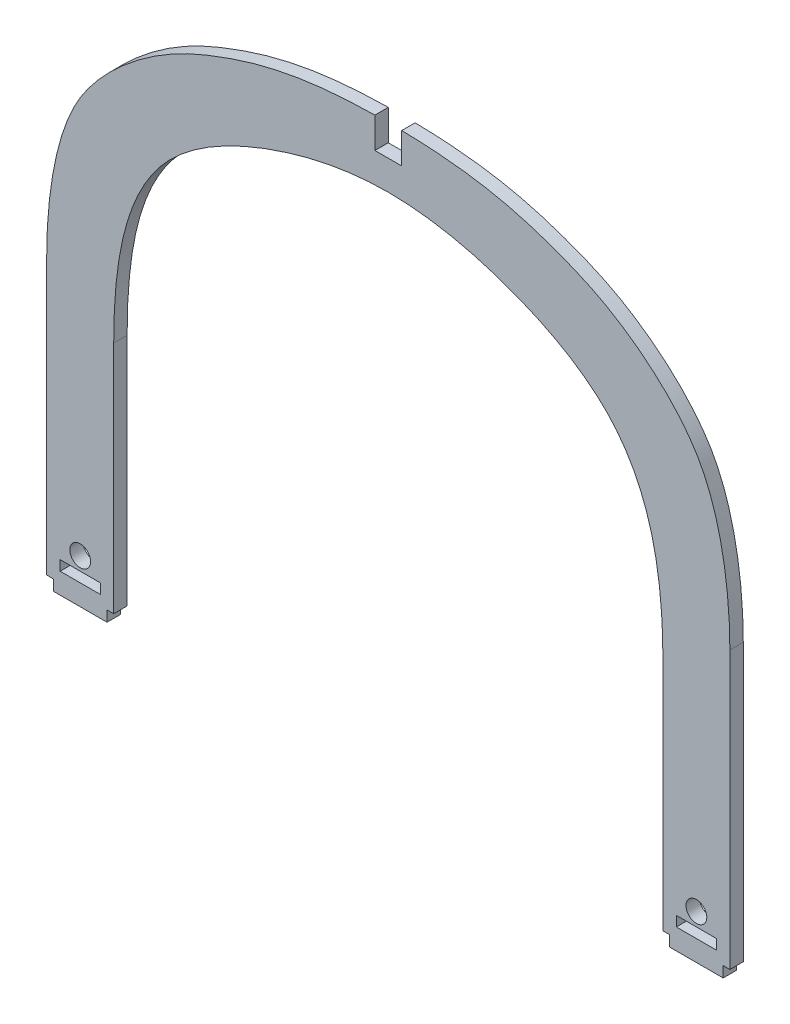
SolidWorks part; units mm, degrees
ref_plane "前视基准面" through (0, 0, 0) normal (0, 0, 1) x (1, 0, 0)
ref_plane "上视基准面" through (0, 0, 0) normal (0, 1, 0) x (1, 0, 0)
ref_plane "右视基准面" through (0, 0, 0) normal (1, 0, 0) x (0, 0, -1)
sketch "草图1" plane through (0, 0, 0) normal (0, 0, 1) x (1, 0, 0)
  line L0 (0, 0) -> (1, 0)
  line L1 (10, 0) -> (10, 35)
  line L2 (0, 0) -> (0, 41.3187)
  line L3 (10, 0) -> (92, 0) construction
  line L4 (51, 0) -> (51, 91.6216) construction
  line L5 (92, 35) -> (92, 0)
  line L6 (92, 0) -> (93, 0)
  line L7 (102, 0) -> (102, 41.3187)
  line L8 (93, -1.6) -> (101, -1.6)
  line L9 (101, -1.6) -> (101, 0)
  line L10 (93, -1.6) -> (93, 0)
  line L11 (9, -1.6) -> (9, 0)
  line L12 (9, -1.6) -> (1, -1.6)
  line L13 (1, -1.6) -> (1, 0)
  line L14 (101, 0) -> (102, 0)
  line L15 (9, 0) -> (10, 0)
  spline S0 degree 3 poles (0, 41.3187) (0, 48.3906) (1.3251, 58.8307) (8.6719, 69.8334) (16.3976, 76.0794) (30.7396, 82.0516) (39.3613, 84) (51, 84) knots 0 0 0 0 0.315307 0.38076 0.624111 0.689077 1 1 1 1
  spline S1 degree 3 poles (102, 41.3187) (102, 48.3906) (100.6749, 58.8307) (93.3281, 69.8334) (85.6024, 76.0794) (71.2604, 82.0516) (62.6387, 84) (51, 84) knots 0 0 0 0 0.315307 0.38076 0.624111 0.689077 1 1 1 1
  spline S2 degree 3 poles (92, 35) (92, 45.9589) (89.1979, 61.8504) (68.861, 72.6058) (56.8497, 75) (51, 75) knots 0 0 0 0 0.441101 0.721666 1 1 1 1
  spline S3 degree 3 poles (10, 35) (10, 45.9589) (12.8021, 61.8504) (33.139, 72.6058) (45.1503, 75) (51, 75) knots 0 0 0 0 0.441101 0.721666 1 1 1 1
  point P15 (97, -1.6)
  dimension "D1" = 10
  dimension "D2" = 35
  dimension "D3" = 82
  dimension "D4" = 8
  dimension "D5" = 1
  dimension "D6" = 1.6
  dimension "D7" = 9
  dimension "D8" = 40
extrude "保护罩主体" add sketch "草图1" along normal blind 2
sketch "上槽口" plane through (0, 0, 0) normal (0, 0, -1) x (-1, 0, 0)
  line L0 (-53, 79.4) -> (-49, 79.4)
  line L1 (-49, 79.4) -> (-49, 86)
  line L4 (-10, 35) -> (-92, 35) construction
  line L5 (-51, 35) -> (-51, 58.4038) construction
  line L6 (-49, 86) -> (-53, 86)
  line L7 (-53, 86) -> (-53, 79.4)
  dimension "D1" = 2
  dimension "D2" = 4
  dimension "D3" = 4.6
extrude "错孔_上" cut sketch "上槽口" against normal through all
sketch "安装孔" plane through (0, 0, 0) normal (0, 0, -1) x (-1, 0, 0)
  line L0 (-92, 0) -> (-93, 0) construction
  line L1 (-51, 86) -> (-51, -18.3042) construction
  line L2 (-92, 35) -> (-92, 0) construction
  circle A0 centre (-97, 5) radius 1.55
  circle A2 centre (-5, 5) radius 1.55
  dimension "D1" = 5
  dimension "D2" = 3.1
  dimension "D3" = 5
extrude "安装孔_" cut sketch "安装孔" against normal through all
sketch "草图4" plane through (0, 0, 0) normal (0, 0, -1) x (-1, 0, 0)
  line L0 (-100, 1.5) -> (-94, 1.5)
  line L1 (-94, 1.5) -> (-94, 3)
  line L2 (-94, 3) -> (-100, 3)
  line L8 (-100, 3) -> (-100, 1.5)
  line L9 (-101, 0) -> (-102, 0) construction
  line L11 (-93, 0) -> (-93, -1.6) construction
  line L12 (-92, 0) -> (-10, 0) construction
  line L13 (-51, 0) -> (-51, 26.9655) construction
  line L14 (-8, 1.5) -> (-8, 3)
  line L15 (-2, 1.5) -> (-8, 1.5)
  line L16 (-2, 3) -> (-2, 1.5)
  line L17 (-8, 3) -> (-2, 3)
  dimension "D1" = 6
  dimension "D2" = 1.5
  dimension "D3" = 1.5
  dimension "D4" = 1
extrude "安装压板过孔" cut sketch "草图4" against normal through all
